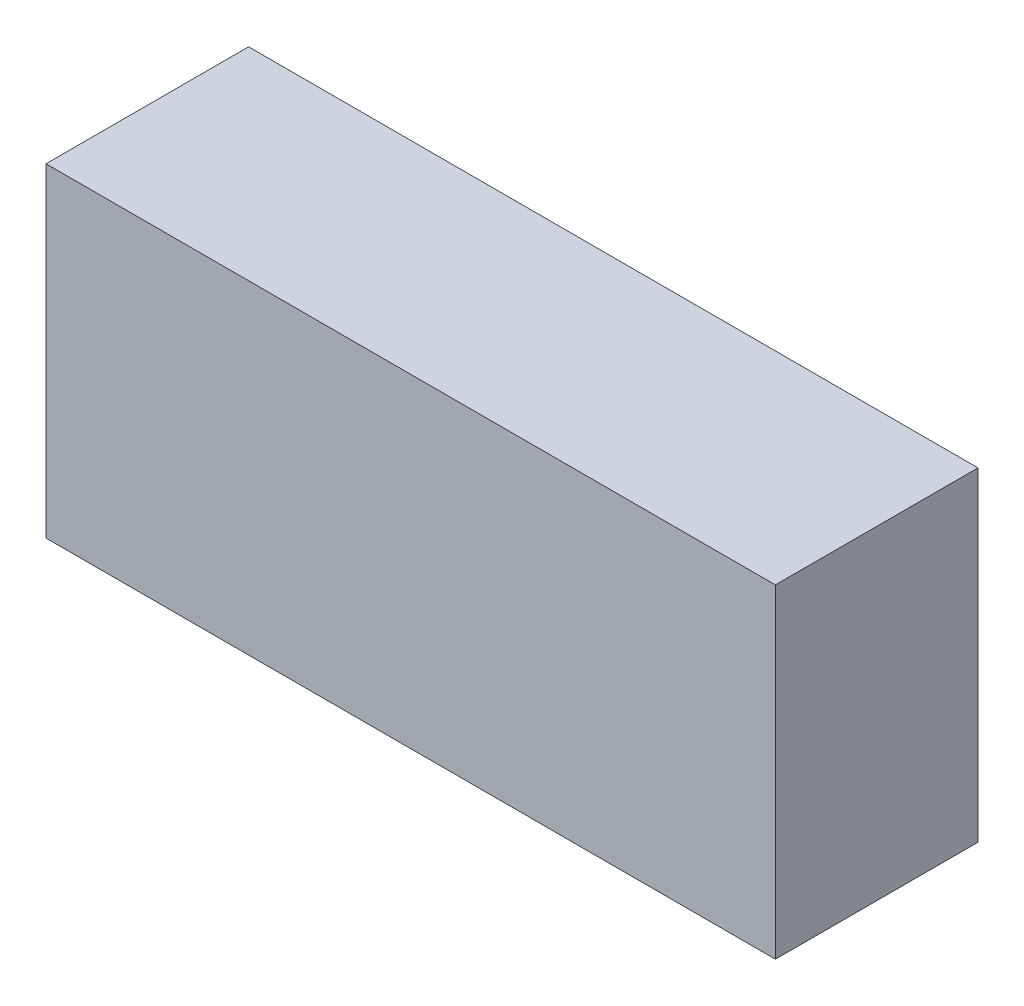
SolidWorks part; units mm, degrees
ref_plane "前视基准面" through (0, 0, 0) normal (0, 0, 1) x (1, 0, 0)
ref_plane "上视基准面" through (0, 0, 0) normal (0, 1, 0) x (1, 0, 0)
ref_plane "右视基准面" through (0, 0, 0) normal (1, 0, 0) x (0, 0, -1)
sketch "草图1" plane through (0, 0, 0) normal (0, 0, 1) x (1, 0, 0)
  line L1 (-36, 16) -> (36, 16)
  line L2 (-36, 16) -> (-36, -16)
  line L3 (-36, -16) -> (36, -16)
  line L4 (36, 16) -> (36, -16)
  line L5 (-36, 16) -> (36, -16) construction
  line L6 (-36, -16) -> (36, 16) construction
  point P0 (0, 0)
  dimension "D1" = 72
  dimension "D2" = 32
extrude "凸台-拉伸1" add sketch "草图1" along normal mid plane 20
